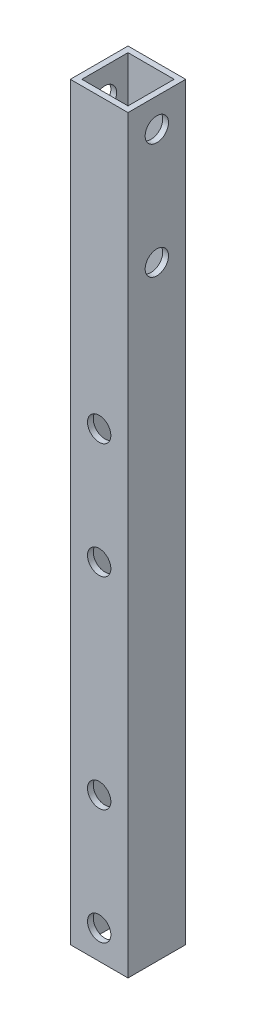
SolidWorks part; units mm, degrees
material "1345 Alloy"
ref_plane "Front Plane" through (0, 0, 0) normal (0, 0, 1) x (1, 0, 0)
ref_plane "Top Plane" through (0, 0, 0) normal (0, 1, 0) x (1, 0, 0)
ref_plane "Right Plane" through (0, 0, 0) normal (1, 0, 0) x (0, 0, -1)
sketch "Sketch1" plane through (0, 0, 0) normal (0, 1, 0) x (1, 0, 0)
  line L1 (-5, 5) -> (5, 5)
  line L2 (-5, 5) -> (-5, -5)
  line L3 (-5, -5) -> (5, -5)
  line L4 (5, 5) -> (5, -5)
  line L5 (-5, 5) -> (5, -5) construction
  line L6 (-5, -5) -> (5, 5) construction
  line L7 (-4, 4) -> (4, 4)
  line L8 (-4, 4) -> (-4, -4)
  line L9 (-4, -4) -> (4, -4)
  line L10 (4, 4) -> (4, -4)
  line L11 (-4, 4) -> (4, -4) construction
  line L12 (-4, -4) -> (4, 4) construction
  point P0 (0, 0)
  point P6 (0, 0)
  dimension "D1" = 10
  dimension "D2" = 10
  dimension "D3" = 8
  dimension "D4" = 8
extrude "Boss-Extrude1" add sketch "Sketch1" along normal blind 130
sketch "Sketch2" plane through (0, 0, 5) normal (0, 0, 1) x (1, 0, 0)
  line L0 (0, -4.9732) -> (0, 56.9204) construction
  line L1 (-5, 0) -> (5, 0) construction
  circle A0 centre (0, 5) radius 2.025
  circle A1 centre (0, 25) radius 2.025
  dimension "D3" = 4.05
  dimension "D4" = 4.05
  dimension "D1" = 20
  dimension "D2" = 5
extrude "Cut-Extrude1" cut sketch "Sketch2" against normal through all
sketch "Sketch3" plane through (5, 0, 0) normal (1, 0, 0) x (0, 0, -1)
  line L0 (0, 137.941) -> (0, -6.8898) construction
  line L1 (-5, 130) -> (5, 130) construction
  circle A0 centre (0, 125) radius 2.025
  circle A1 centre (0, 105) radius 2.025
  point P7 (0, 123.3412)
  point P8 (0, 137.941)
  point P9 (0, 123.458)
  dimension "D1" = 4.05
  dimension "D2" = 4.05
  dimension "D3" = 20
  dimension "D4" = 5
extrude "Cut-Extrude2" cut sketch "Sketch3" against normal through all
sketch "Sketch4" plane through (0, 0, 5) normal (0, 0, 1) x (1, 0, 0)
  line L0 (0, -3.7363) -> (0, 132.9187) construction
  circle A0 centre (0, 60) radius 2.025
  circle A1 centre (0, 80) radius 2.025
  dimension "D1" = 4.05
  dimension "D2" = 4.05
  dimension "D3" = 20
  dimension "D4" = 60
extrude "Cut-Extrude3" cut sketch "Sketch4" against normal through all
